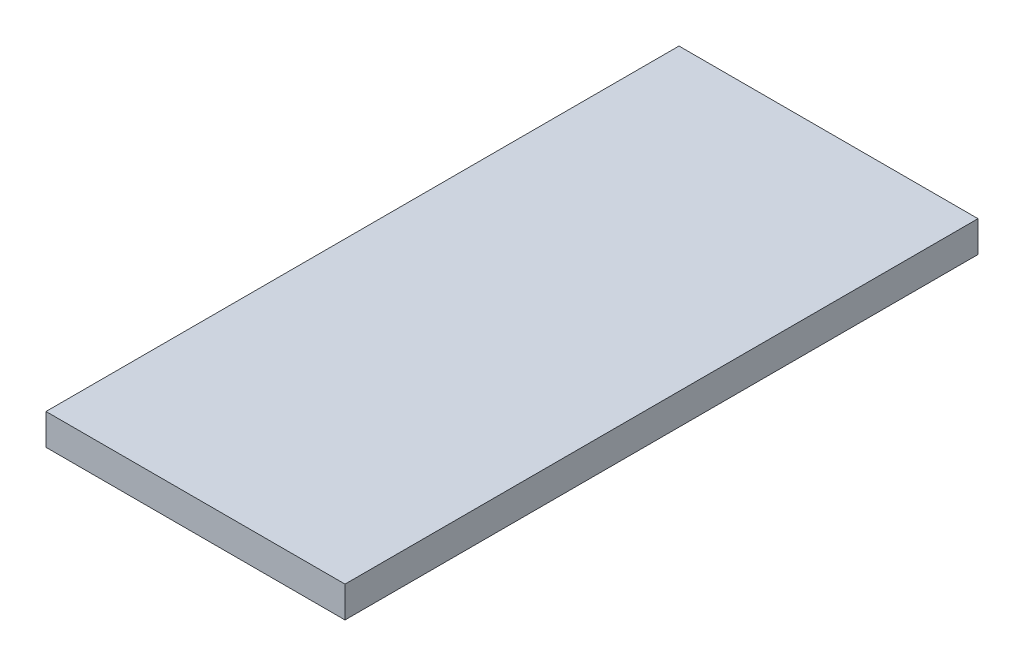
SolidWorks part; units mm, degrees
ref_plane "前视基准面" through (0, 0, 0) normal (0, 0, 1) x (1, 0, 0)
ref_plane "上视基准面" through (0, 0, 0) normal (0, 1, 0) x (1, 0, 0)
ref_plane "右视基准面" through (0, 0, 0) normal (1, 0, 0) x (0, 0, -1)
other "Configuration Table"
sketch "草图1" plane through (0, 0, 0) normal (0, 1, 0) x (1, 0, 0)
  line L1 (0, 0) -> (77, 0)
  line L2 (0, 0) -> (0, -163)
  line L3 (0, -163) -> (77, -163)
  line L4 (77, 0) -> (77, -163)
  dimension "D1" = 163
  dimension "D2" = 77
extrude "凸台-拉伸1" add sketch "草图1" along normal blind 8
